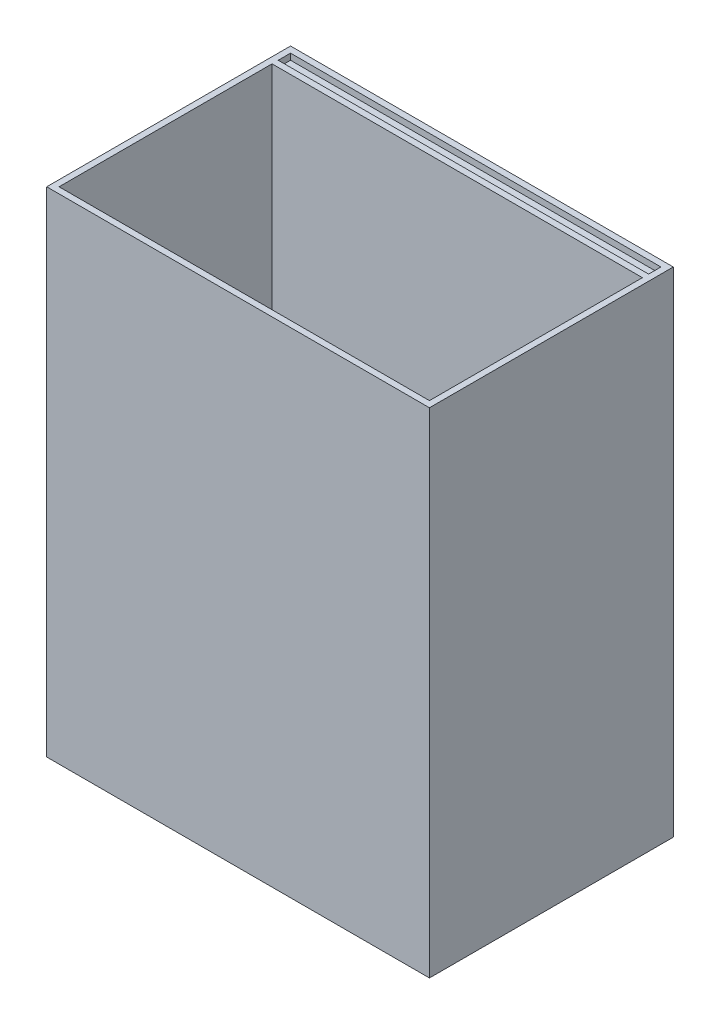
SolidWorks part; units mm, degrees
material "6061-T6 (SS)"
ref_plane "Front Plane" through (0, 0, 0) normal (0, 0, 1) x (1, 0, 0)
ref_plane "Top Plane" through (0, 0, 0) normal (0, 1, 0) x (1, 0, 0)
ref_plane "Right Plane" through (0, 0, 0) normal (1, 0, 0) x (0, 0, -1)
sketch "Sketch1" plane through (0, 0, 0) normal (0, 0, 1) x (1, 0, 0)
  line L1 (0, 0) -> (6200, 0)
  line L2 (0, 0) -> (0, 8000)
  line L3 (0, 8000) -> (6200, 8000)
  line L4 (6200, 0) -> (6200, 8000)
  dimension "D1" = 6200
  dimension "D2" = 8000
extrude "Boss-Extrude1" add sketch "Sketch1" along normal blind 100
sketch "Sketch2" plane through (0, 0, 100) normal (0, 0, 1) x (1, 0, 0)
  line L0 (6200, 0) -> (6200, 8000) construction
  line L1 (0, 0) -> (6200, 0)
  line L2 (0, 0) -> (0, 100)
  line L3 (0, 100) -> (6200, 100)
  line L4 (6200, 0) -> (6200, 100)
  dimension "D1" = 6200
  dimension "D2" = 100
extrude "Boss-Extrude2" add sketch "Sketch2" along normal blind 3850
sketch "Sketch3" plane through (0, 0, 3950) normal (0, 0, 1) x (1, 0, 0)
  line L1 (0, 0) -> (6200, 0)
  line L2 (0, 0) -> (0, 8000)
  line L3 (0, 8000) -> (6200, 8000)
  line L4 (6200, 0) -> (6200, 8000)
  dimension "D1" = 8000
  dimension "D2" = 6200
extrude "Boss-Extrude3" add sketch "Sketch3" against normal blind 100
sketch "Sketch4" plane through (0, 0, 0) normal (0, 0, -1) x (-1, 0, 0)
sketch "Sketch5" plane through (6200, 0, 0) normal (1, 0, 0) x (0, 0, -1)
  line L1 (-3850, 100) -> (-100, 100)
  line L2 (-3850, 100) -> (-3850, 8000)
  line L3 (-3850, 8000) -> (-100, 8000)
  line L4 (-100, 100) -> (-100, 8000)
extrude "Boss-Extrude4" add sketch "Sketch5" against normal blind 100
sketch "Sketch6" plane through (0, 0, 0) normal (-1, 0, 0) x (0, 0, 1)
  line L1 (100, 100) -> (3850, 100)
  line L2 (100, 100) -> (100, 8000)
  line L3 (100, 8000) -> (3850, 8000)
  line L4 (3850, 100) -> (3850, 8000)
extrude "Boss-Extrude5" add sketch "Sketch6" against normal blind 100
sketch "Sketch8" plane through (0, 0, 3850) normal (0, 0, -1) x (-1, 0, 0)
  line L0 (-6100, 8000) -> (-6100, 100) construction
  line L1 (-6100, 1600) -> (0, 1600)
  line L2 (-6100, 1600) -> (-6100, 1401.7231)
  line L3 (-6100, 1401.7231) -> (0, 1401.7231)
  line L4 (0, 1600) -> (0, 1401.7231)
  line L5 (-100, 100) -> (-6100, 100) construction
  dimension "D1" = 1500
extrude "Boss-Extrude7" add sketch "Sketch8" along normal blind 3550
sketch "Sketch9" plane through (0, 1600, 0) normal (0, 1, 0) x (1, 0, 0)
  line L0 (6100, -300) -> (6100, -3850) construction
  line L1 (100, -300) -> (6100, -300)
  line L2 (100, -300) -> (100, -400)
  line L3 (100, -400) -> (6100, -400)
  line L4 (6100, -300) -> (6100, -400)
  dimension "D1" = 100
extrude "Boss-Extrude8" add sketch "Sketch9" along normal blind 6400
sketch "Sketch10" plane through (0, 0, 0) normal (0, -1, 0) x (1, 0, 0)
  line L5 (0, 3950) -> (0, 0) construction
  line L6 (0, 3575) -> (6200, 3575)
  line L7 (0, 3575) -> (0, 3475)
  line L8 (0, 3475) -> (6200, 3475)
  line L9 (6200, 3575) -> (6200, 3475)
  line L10 (6200, 3950) -> (6200, 0) construction
  line L11 (0, 3950) -> (6200, 3950) construction
  line L12 (0, 475) -> (6200, 475)
  line L13 (0, 475) -> (0, 375)
  line L14 (0, 375) -> (6200, 375)
  line L15 (6200, 475) -> (6200, 375)
  line L16 (0, 0) -> (6200, 0) construction
  dimension "D1" = 100
  dimension "D2" = 100
  dimension "D3" = 3000
  dimension "D4" = 475
  dimension "D5" = 475
extrude "Boss-Extrude9" add sketch "Sketch10" against normal blind 1500
sketch "Sketch11" plane through (0, 0, 0) normal (0, 0, -1) x (-1, 0, 0)
  line L0 (-6200, 0) -> (-6200, 8000) construction
  line L1 (-6200, 7900) -> (0, 7900)
  line L2 (-6200, 7900) -> (-6200, 7800)
  line L3 (-6200, 7800) -> (0, 7800)
  line L4 (0, 7900) -> (0, 7800)
  line L5 (0, 8000) -> (0, 0) construction
  line L6 (-6200, 8000) -> (0, 8000) construction
  line L7 (-6200, 5800) -> (0, 5800)
  line L8 (-6200, 5800) -> (-6200, 5700)
  line L9 (-6200, 5700) -> (0, 5700)
  line L10 (0, 5800) -> (0, 5700)
  line L12 (-6200, 5200) -> (0, 5200)
  line L13 (-6200, 5200) -> (-6200, 5100)
  line L14 (-6200, 5100) -> (0, 5100)
  line L15 (0, 5200) -> (0, 5100)
  dimension "D1" = 100
  dimension "D2" = 100
  dimension "D3" = 2000
  dimension "D4" = 100
  dimension "D5" = 100
  dimension "D6" = 500
extrude "Boss-Extrude11" add sketch "Sketch11" against normal blind 300
sketch "Sketch12" plane through (0, 0, 0) normal (0, 1, 0) x (1, 0, 0)
  line L1 (0, 0) -> (6200, 0)
  line L2 (0, 0) -> (0, -3950)
  line L3 (0, -3950) -> (6200, -3950)
  line L4 (6200, 0) -> (6200, -3950)
extrude "Cut-Extrude2" [suppressed] cut sketch "Sketch12" along normal blind 100
